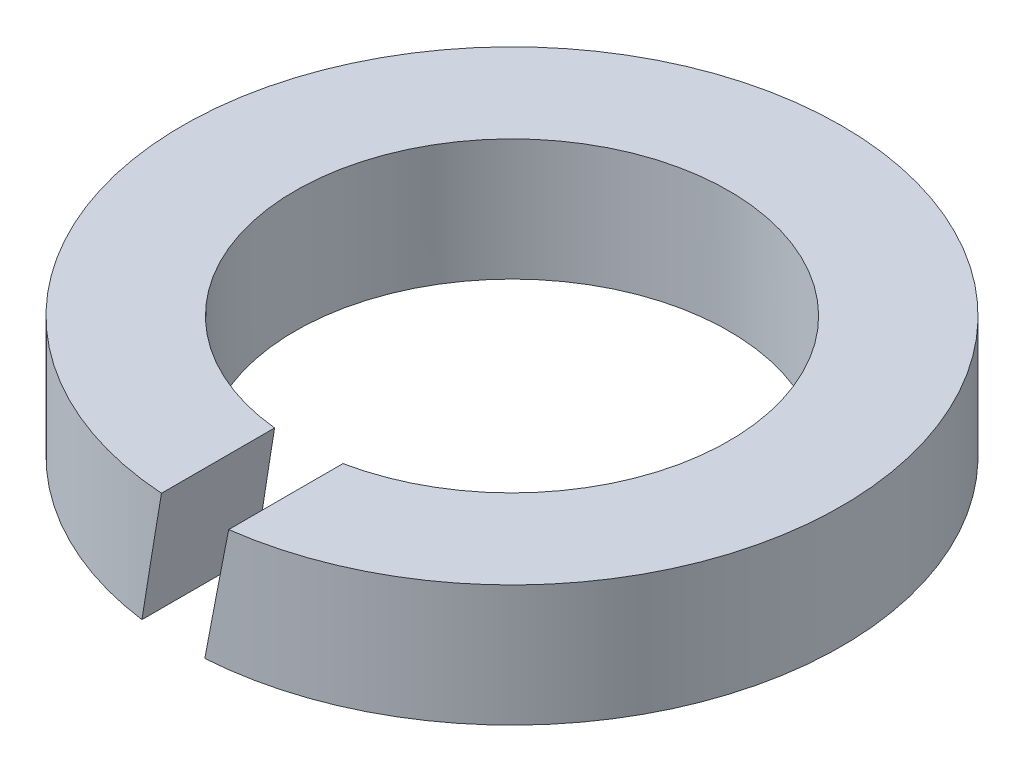
SolidWorks part; units mm, degrees
material "AISI 304"
ref_plane "前视基准面" through (0, 0, 0) normal (0, 0, 1) x (1, 0, 0)
ref_plane "上视基准面" through (0, 0, 0) normal (0, 1, 0) x (1, 0, 0)
ref_plane "右视基准面" through (0, 0, 0) normal (1, 0, 0) x (0, 0, -1)
sketch "草图1" plane through (0, 0, 0) normal (0, 1, 0) x (1, 0, 0)
  circle A0 centre (0, 0) radius 2.5
  circle A1 centre (0, 0) radius 3.8
  point P4 (2.5, 0)
  point P5 (3.8, 0)
  dimension "D1" = 5
  dimension "D2" = 1.3
extrude "凸台-拉伸1" add sketch "草图1" along normal blind 1.4
sketch "草图2" plane through (0, 0, 0) normal (0, 0, 1) x (1, 0, 0)
  line L0 (0, 1.3469) -> (0, -0.9057) construction
  line L2 (3.8, 1.4) -> (-3.8, 1.4) construction
  line L3 (3.8, 1.4) -> (-3.8, 1.4) construction
  line L4 (-0.5, 0) -> (-0.25, 1.4)
  line L6 (0.25, 0) -> (0.5, 1.4)
  line L7 (0.5, 1.4) -> (-0.25, 1.4)
  line L8 (-0.5, 0) -> (0.25, 0)
  dimension "D1" = 0.75
  dimension "D2" = 0.25
  dimension "D3" = 0.25
extrude "切除-拉伸1" cut sketch "草图2" along normal through all
equation "\"内径\" = 5"
equation "\"厚\" = 1.4"
equation "\"圈宽\"= 1.3"
equation "\"D1@草图1\"= \"内径\""
equation "\"D2@草图1\"= \"圈宽\""
equation "\"D1@凸台-拉伸1\"= \"厚\""
equation "\"D1@草图2\"=0.15 * \"内径\""
equation "\"D2@草图2\"= 0.05 * \"内径\""
equation "\"D3@草图2\"= 0.05 * \"内径\""
